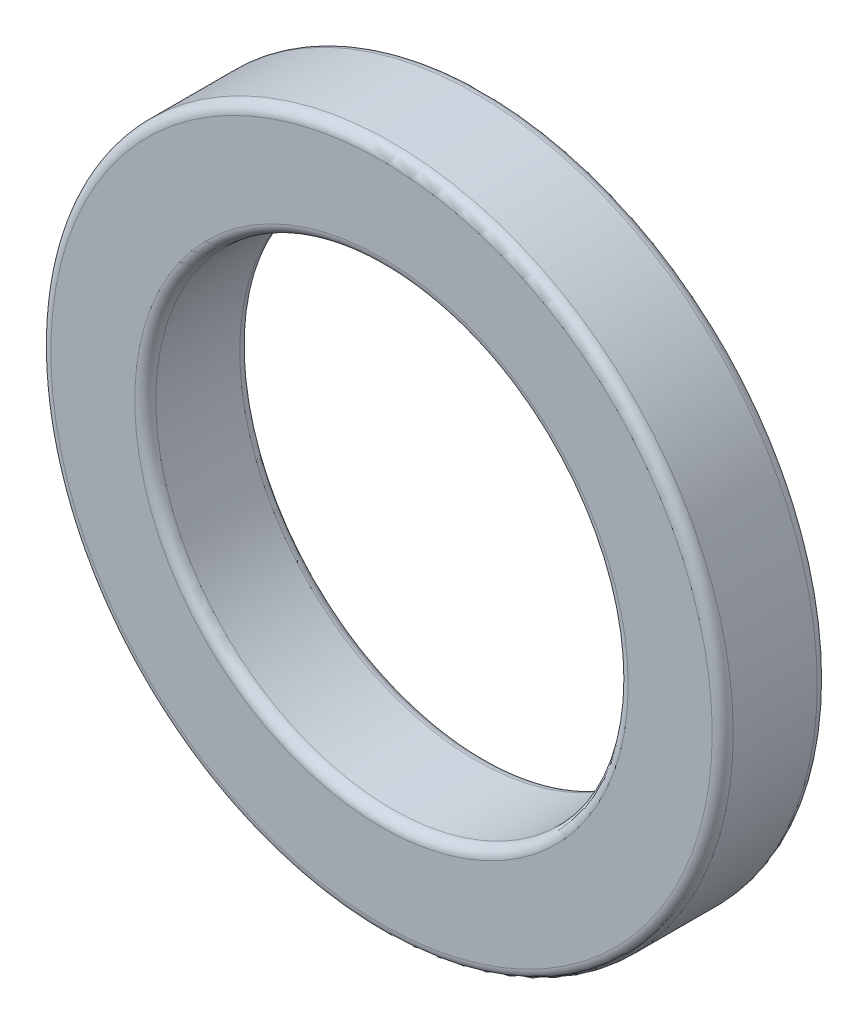
SolidWorks part; units mm, degrees
ref_plane "Front Plane" through (0, 0, 0) normal (0, 0, 1) x (1, 0, 0)
ref_plane "Top Plane" through (0, 0, 0) normal (0, 1, 0) x (1, 0, 0)
ref_plane "Right Plane" through (0, 0, 0) normal (1, 0, 0) x (0, 0, -1)
sketch "Sketch1" plane through (0, 0, 0) normal (0, 0, 1) x (1, 0, 0)
  circle A0 centre (0, 0) radius 4.5
  circle A1 centre (0, 0) radius 6.5
  dimension "D1" = 2
extrude "Boss-Extrude1" add sketch "Sketch1" along normal blind 2
fillet "Fillet1" radius 0.2 4 edges at (6.5, 0, 0) (6.5, 0, 2) (4.5, 0, 0) (4.5, 0, 2)
